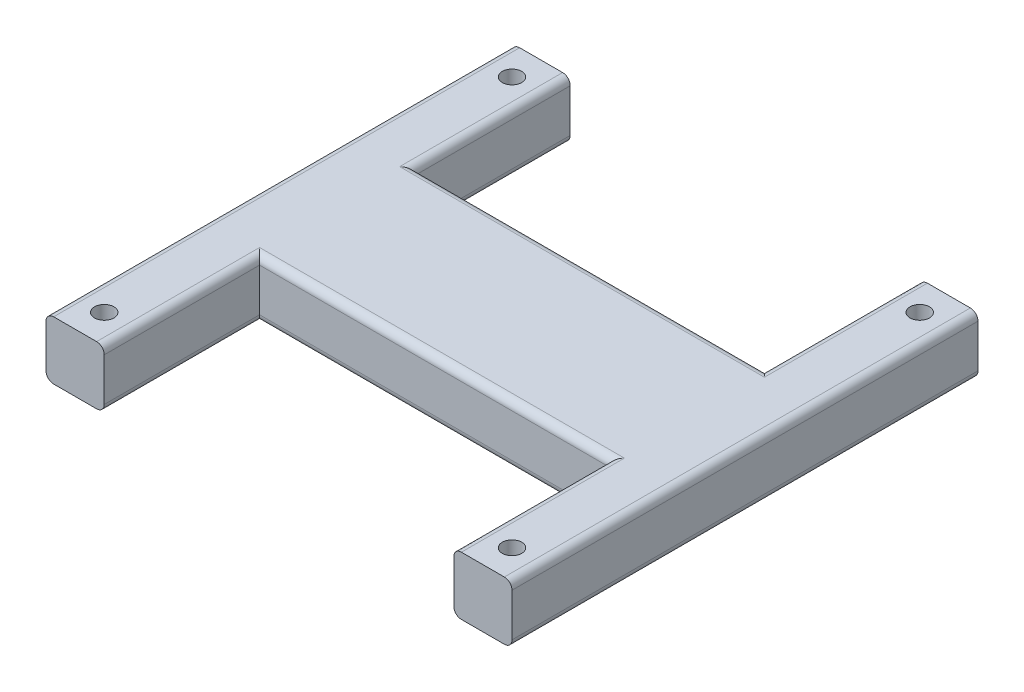
SolidWorks part; units mm, degrees
ref_plane "Front Plane" through (0, 0, 0) normal (0, 0, 1) x (1, 0, 0)
ref_plane "Top Plane" through (0, 0, 0) normal (0, 1, 0) x (1, 0, 0)
ref_plane "Right Plane" through (0, 0, 0) normal (1, 0, 0) x (0, 0, -1)
sketch "Sketch1" plane through (0, 0, 0) normal (0, 1, 0) x (1, 0, 0)
  line L1 (-304.8, -304.8) -> (304.8, -304.8)
  line L2 (-304.8, -304.8) -> (-304.8, 304.8)
  line L3 (-304.8, 304.8) -> (304.8, 304.8)
  line L4 (304.8, -304.8) -> (304.8, 304.8)
  line L5 (-304.8, -304.8) -> (304.8, 304.8) construction
  line L6 (-304.8, 304.8) -> (304.8, -304.8) construction
  point P0 (0, 0)
extrude "Boss-Extrude1" add sketch "Sketch1" along normal blind 76.2
sketch "Sketch2" plane through (0, 76.2, 0) normal (0, 1, 0) x (1, 0, 0)
  line L3 (-304.8, -304.8) -> (304.8, -304.8) construction
  line L5 (304.8, 304.8) -> (-304.8, 304.8) construction
  line L6 (-228.6, -304.8) -> (228.6, -304.8)
  line L7 (-228.6, -304.8) -> (-228.6, -101.6)
  line L8 (-228.6, -101.6) -> (228.6, -101.6)
  line L9 (228.6, -304.8) -> (228.6, -101.6)
  line L10 (-228.6, 304.8) -> (228.6, 304.8)
  line L11 (-228.6, 304.8) -> (-228.6, 101.6)
  line L12 (-228.6, 101.6) -> (228.6, 101.6)
  line L13 (228.6, 304.8) -> (228.6, 101.6)
  dimension "D1" = 203.2
  dimension "D2" = 203.2
extrude "Cut-Extrude1" cut sketch "Sketch2" against normal blind 76.2
sketch "Sketch3" plane through (0, 76.2, 0) normal (0, 1, 0) x (1, 0, 0)
  line L0 (-228.6, 304.8) -> (-304.8, 304.8) construction
  circle A0 centre (-266.7, 266.7) radius 12.7
  dimension "D1" = 38.1
extrude "Cut-Extrude2" cut sketch "Sketch3" against normal blind 38.1
mirror "Mirror1" about plane through (0, 0, 0) normal (1, 0, 0) of "Cut-Extrude2" second plane through (0, 0, 0) second plane normal (0, 0, 1)
sketch "Sketch6" plane through (0, 0, 0) normal (0, -1, 0) x (1, 0, 0)
  circle A0 centre (0, 0) radius 74.93
extrude "Cut-Extrude3" cut sketch "Sketch6" against normal blind 6.35
fillet "Fillet1" radius 2.54 1 edges at (0, 0, -74.93)
sketch "Sketch7" plane through (0, 0, 0) normal (0, -1, 0) x (1, 0, 0)
  line L0 (0, -41.91) -> (0, 41.91) construction
  circle A0 centre (0, 66) radius 4.4958
  dimension "D1" = 66
extrude "Cut-Extrude4" cut sketch "Sketch7" against normal blind 20
pattern_circular "CirPattern1" count 4 every 90 about axis through (0, 0, 0) along (0, 1, 0) of "Cut-Extrude4"
fillet "Fillet2" radius 10 16 edges at (0, 76.2, 101.6) (0, 76.2, -101.6) (304.8, 76.2, 0) (228.6, 76.2, 203.2) (228.6, 76.2, -203.2) (-228.6, 76.2, -203.2) (-228.6, 76.2, 203.2) (-304.8, 76.2, 0) (0, 0, -101.6) (0, 0, 101.6) (228.6, 0, -203.2) (228.6, 0, 203.2) (-228.6, 0, -203.2) (-228.6, 0, 203.2) (-304.8, 0, 0) (304.8, 0, 0)
